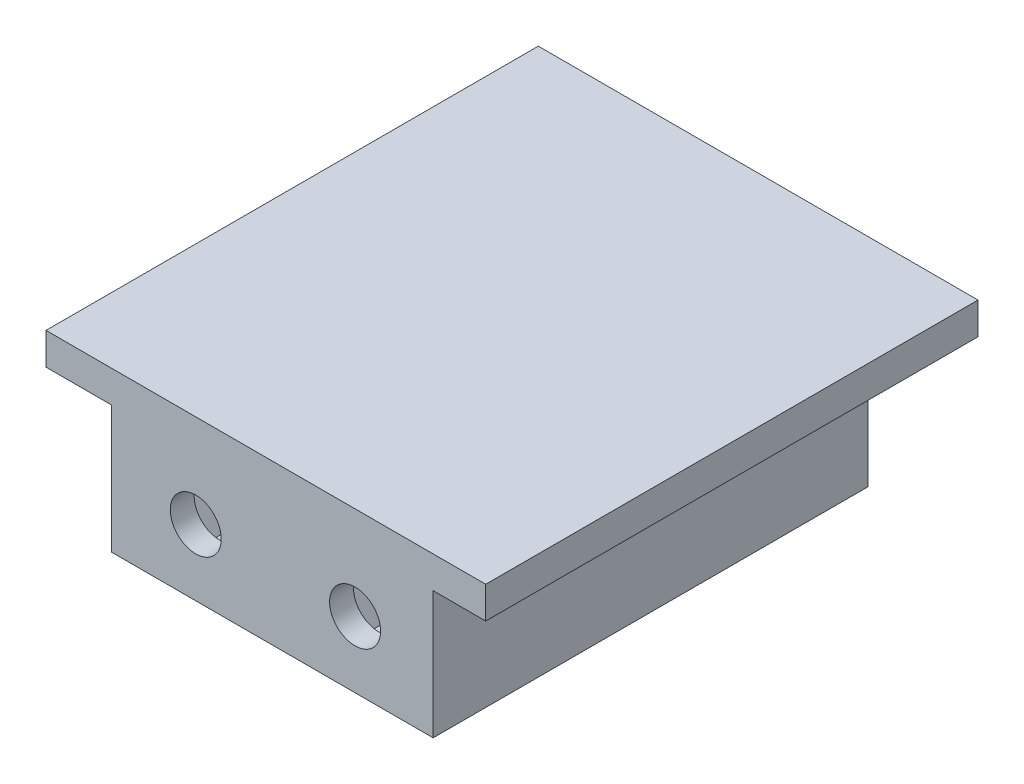
SolidWorks part; units mm, degrees
ref_plane "Front Plane" through (0, 0, 0) normal (0, 0, 1) x (1, 0, 0)
ref_plane "Top Plane" through (0, 0, 0) normal (0, 1, 0) x (1, 0, 0)
ref_plane "Right Plane" through (0, 0, 0) normal (1, 0, 0) x (0, 0, -1)
sketch "Sketch1" plane through (0, 0, 0) normal (0, 1, 0) x (1, 0, 0)
  line L1 (11.8589, 17.0866) -> (39.4589, 17.0866)
  line L2 (11.8589, 17.0866) -> (11.8589, -13.8134)
  line L3 (11.8589, -13.8134) -> (39.4589, -13.8134)
  line L4 (39.4589, 17.0866) -> (39.4589, -13.8134)
  dimension "D1" = 30.9
  dimension "D2" = 27.6
extrude "Boss-Extrude1" add sketch "Sketch1" along normal blind 2
sketch "Sketch2" plane through (0, 0, 0) normal (0, -1, 0) x (1, 0, 0)
  line L0 (11.8589, 13.8134) -> (39.4589, 13.8134) construction
  line L1 (15.9589, 13.8134) -> (36.1589, 13.8134)
  line L2 (15.9589, 13.8134) -> (15.9589, -13.4866)
  line L3 (15.9589, -13.4866) -> (36.1589, -13.4866)
  line L4 (36.1589, 13.8134) -> (36.1589, -13.4866)
  line L5 (39.4589, -17.0866) -> (11.8589, -17.0866) construction
  line L7 (11.8589, -17.0866) -> (11.8589, 13.8134) construction
  line L9 (39.4589, 13.8134) -> (39.4589, -17.0866) construction
  dimension "D1" = 3.6
  dimension "D2" = 3.3
  dimension "D3" = 4.1
extrude "Boss-Extrude2" add sketch "Sketch2" along normal blind 8
sketch "Sketch3" plane through (0, 0, 13.8134) normal (0, 0, 1) x (1, 0, 0)
  circle A0 centre (21.2589, -3.85) radius 1.6
  circle A1 centre (31.2589, -3.85) radius 1.6
  dimension "D1" = 3.2
  dimension "D2" = 3.2
extrude "Cut-Extrude1" cut sketch "Sketch3" against normal blind 32
ref_plane "Plane1" through (0, 0, 12.3134) normal (0, 0, 1) x (1, 0, 0)
sketch "Sketch4" plane through (0, 0, 12.3134) normal (0, 0, 1) x (1, 0, 0)
  line L1 (32.9909, -6.85) -> (34.723, -3.85)
  line L2 (34.723, -3.85) -> (32.9909, -0.85)
  line L3 (32.9909, -0.85) -> (29.5268, -0.85)
  line L4 (29.5268, -0.85) -> (27.7948, -3.85)
  line L5 (27.7948, -3.85) -> (29.5268, -6.85)
  line L6 (29.5268, -6.85) -> (32.9909, -6.85)
  line L7 (23.0386, -6.8219) -> (24.7225, -3.7947)
  line L8 (24.7225, -3.7947) -> (22.9428, -0.8227)
  line L9 (22.9428, -0.8227) -> (19.4791, -0.8781)
  line L10 (19.4791, -0.8781) -> (17.7952, -3.9053)
  line L11 (17.7952, -3.9053) -> (19.575, -6.8773)
  line L12 (19.575, -6.8773) -> (23.0386, -6.8219)
  circle A0 centre (31.2589, -3.85) radius 3 construction
  circle A1 centre (21.2589, -3.85) radius 3 construction
extrude "Cut-Extrude2" cut sketch "Sketch4" against normal blind 2.5
ref_plane "Plane2" through (0, 0, -11.9866) normal (0, 0, -1) x (-1, 0, 0)
sketch "Sketch5" plane through (0, 0, -11.9866) normal (0, 0, -1) x (-1, 0, 0)
  line L1 (-29.5268, -6.85) -> (-27.7948, -3.85)
  line L2 (-27.7948, -3.85) -> (-29.5268, -0.85)
  line L3 (-29.5268, -0.85) -> (-32.9909, -0.85)
  line L4 (-32.9909, -0.85) -> (-34.723, -3.85)
  line L5 (-34.723, -3.85) -> (-32.9909, -6.85)
  line L6 (-32.9909, -6.85) -> (-29.5268, -6.85)
  line L7 (-19.5268, -6.85) -> (-17.7948, -3.85)
  line L8 (-17.7948, -3.85) -> (-19.5268, -0.85)
  line L9 (-19.5268, -0.85) -> (-22.9909, -0.85)
  line L10 (-22.9909, -0.85) -> (-24.723, -3.85)
  line L11 (-24.723, -3.85) -> (-22.9909, -6.85)
  line L12 (-22.9909, -6.85) -> (-19.5268, -6.85)
  circle A0 centre (-31.2589, -3.85) radius 3 construction
  circle A1 centre (-21.2589, -3.85) radius 3 construction
extrude "Cut-Extrude3" cut sketch "Sketch5" against normal blind 2.5
